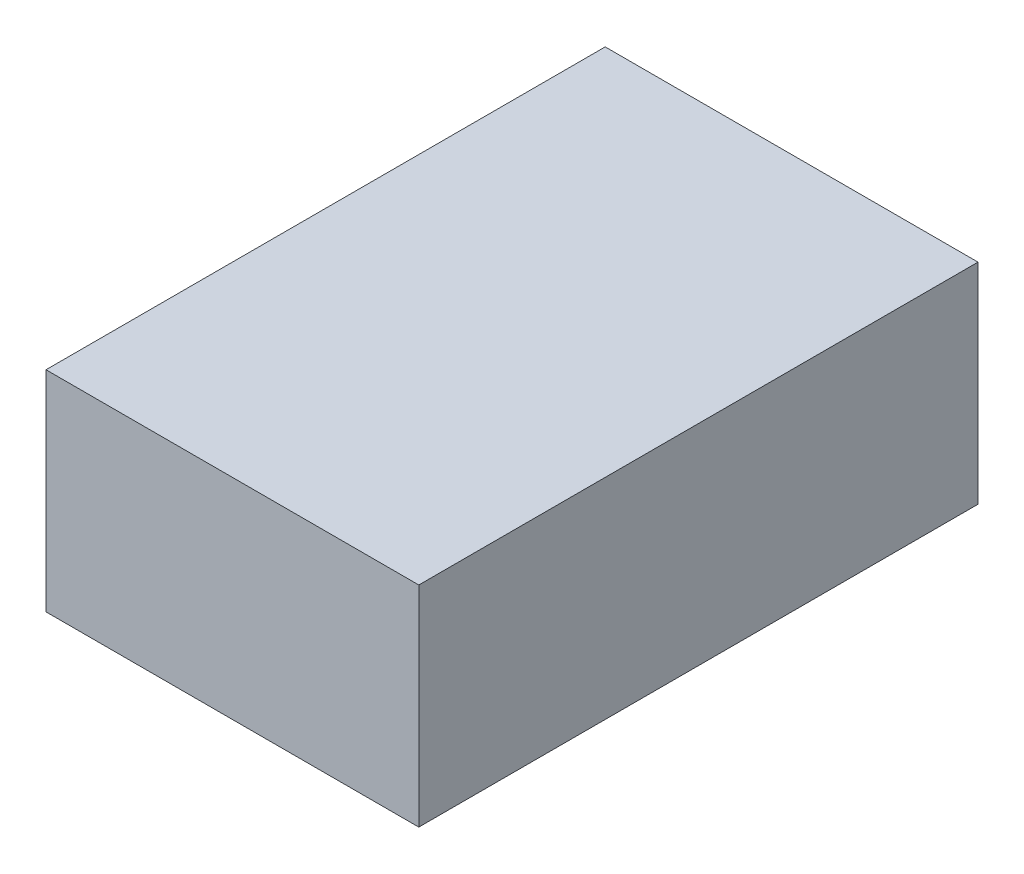
SolidWorks part; units mm, degrees
ref_plane "Front Plane" through (0, 0, 0) normal (0, 0, 1) x (1, 0, 0)
ref_plane "Top Plane" through (0, 0, 0) normal (0, 1, 0) x (1, 0, 0)
ref_plane "Right Plane" through (0, 0, 0) normal (1, 0, 0) x (0, 0, -1)
sketch "Sketch1" plane through (0, 0, 0) normal (0, 0, 1) x (1, 0, 0)
  line L2 (-25.4, -14.2875) -> (25.4, -14.2875)
  line L3 (-25.4, -14.2875) -> (-25.4, 14.2875)
  line L4 (-25.4, 14.2875) -> (25.4, 14.2875)
  line L5 (25.4, -14.2875) -> (25.4, 14.2875)
  line L6 (-25.4, -14.2875) -> (25.4, 14.2875) construction
  line L7 (-25.4, 14.2875) -> (25.4, -14.2875) construction
  point P2 (0, 0)
  dimension "D1" = 28.575
  dimension "D2" = 50.8
extrude "Boss-Extrude1" add sketch "Sketch1" against normal blind 76.2
